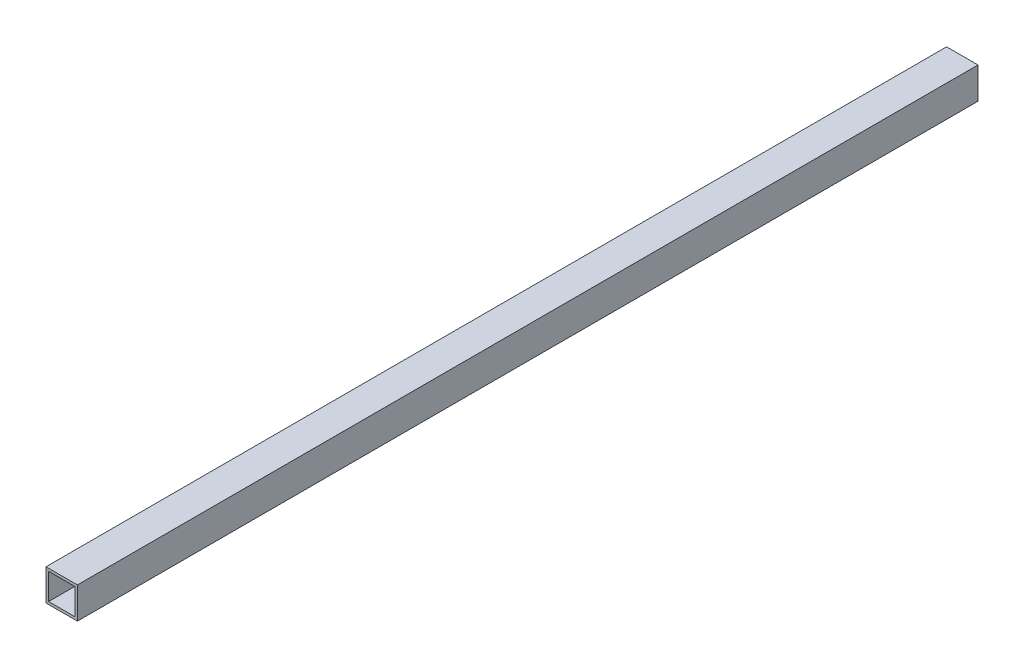
SolidWorks part; units mm, degrees
material "6063-T6"
ref_plane "Front Plane" through (0, 0, 0) normal (0, 0, 1) x (1, 0, 0)
ref_plane "Top Plane" through (0, 0, 0) normal (0, 1, 0) x (1, 0, 0)
ref_plane "Right Plane" through (0, 0, 0) normal (1, 0, 0) x (0, 0, -1)
sketch "Sketch1" plane through (0, 0, 0) normal (0, 0, 1) x (1, 0, 0)
  line L1 (9.525, -9.525) -> (-9.525, -9.525)
  line L2 (9.525, -9.525) -> (9.525, 9.525)
  line L3 (9.525, 9.525) -> (-9.525, 9.525)
  line L4 (-9.525, -9.525) -> (-9.525, 9.525)
  line L5 (9.525, -9.525) -> (-9.525, 9.525) construction
  line L6 (9.525, 9.525) -> (-9.525, -9.525) construction
  line L7 (7.9375, -7.9375) -> (-7.9375, -7.9375)
  line L8 (7.9375, -7.9375) -> (7.9375, 7.9375)
  line L9 (7.9375, 7.9375) -> (-7.9375, 7.9375)
  line L10 (-7.9375, -7.9375) -> (-7.9375, 7.9375)
  line L11 (7.9375, -7.9375) -> (-7.9375, 7.9375) construction
  line L12 (7.9375, 7.9375) -> (-7.9375, -7.9375) construction
  point P0 (0, 0)
  point P5 (0, 0)
  dimension "D1" = 19.05
  dimension "D2" = 19.05
  dimension "D3" = 1.5875
extrude "Boss-Extrude1" add sketch "Sketch1" along normal mid plane 546.1
